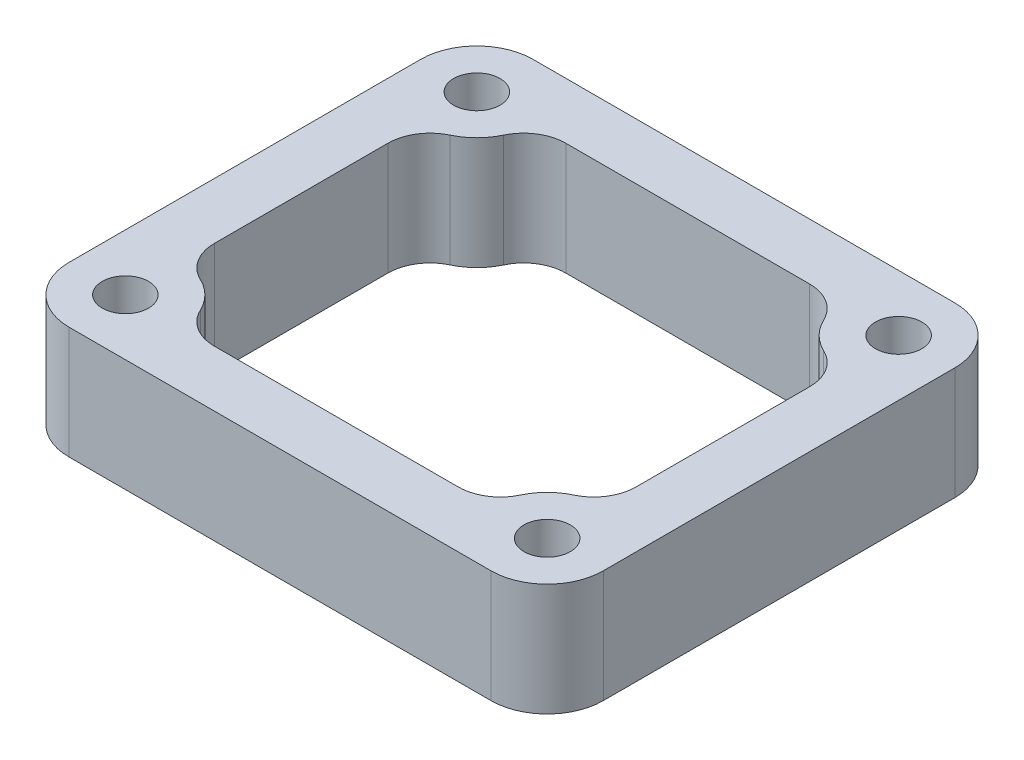
SolidWorks part; units mm, degrees
material "6061 合金"
ref_plane "前视基准面" through (0, 0, 0) normal (0, 0, 1) x (1, 0, 0)
ref_plane "上视基准面" through (0, 0, 0) normal (0, 1, 0) x (1, 0, 0)
ref_plane "右视基准面" through (0, 0, 0) normal (1, 0, 0) x (0, 0, -1)
other "Configuration Table"
sketch "草图1" plane through (0, 0, 0) normal (0, 1, 0) x (1, 0, 0)
  line L0 (-19, 12.5) -> (-19, -12.5)
  line L1 (-15, -12.5) -> (15, -12.5) construction
  line L2 (-15, -12.5) -> (-15, 12.5) construction
  line L3 (-15, 12.5) -> (15, 12.5) construction
  line L4 (15, -12.5) -> (15, 12.5) construction
  line L5 (-15, -12.5) -> (15, 12.5) construction
  line L6 (-15, 12.5) -> (15, -12.5) construction
  line L7 (-15, 16.5) -> (15, 16.5)
  line L8 (-11, 12.5) -> (11, 12.5)
  line L9 (-15, 8.5) -> (-15, -8.5)
  line L10 (-11, -12.5) -> (11, -12.5)
  line L11 (15, -8.5) -> (15, 8.5)
  line L12 (19, 12.5) -> (19, -12.5)
  line L13 (15, -16.5) -> (-15, -16.5)
  circle A0 centre (-15, 12.5) radius 1.65
  circle A1 centre (15, 12.5) radius 1.65
  circle A2 centre (-15, -12.5) radius 1.65
  circle A3 centre (15, -12.5) radius 1.65
  arc A4 (-15, 8.5) -> (-11, 12.5) centre (-15, 12.5) ccw
  arc A5 (11, 12.5) -> (15, 8.5) centre (15, 12.5) ccw
  arc A6 (-11, -12.5) -> (-15, -8.5) centre (-15, -12.5) ccw
  arc A7 (15, -8.5) -> (11, -12.5) centre (15, -12.5) ccw
  arc A8 (-19, -12.5) -> (-15, -16.5) centre (-15, -12.5) ccw
  arc A9 (-15, 16.5) -> (-19, 12.5) centre (-15, 12.5) ccw
  arc A10 (19, 12.5) -> (15, 16.5) centre (15, 12.5) ccw
  arc A11 (15, -16.5) -> (19, -12.5) centre (15, -12.5) ccw
  point P0 (0, 0)
  dimension "D3" = 3.3
  dimension "D7" = 8
  dimension "D8" = 8
  dimension "D1" = 30
  dimension "D2" = 25
  dimension "D4" = 2
  dimension "D5" = 2
  dimension "D6" = 2
extrude "凸台-拉伸1" add sketch "草图1" along normal blind 8
fillet "圆角1" radius 3 8 edges at (-15, 4, 8.5) (-11, 4, 12.5) (11, 4, 12.5) (15, 4, 8.5) (15, 4, -8.5) (11, 4, -12.5) (-15, 4, -8.5) (-11, 4, -12.5)
